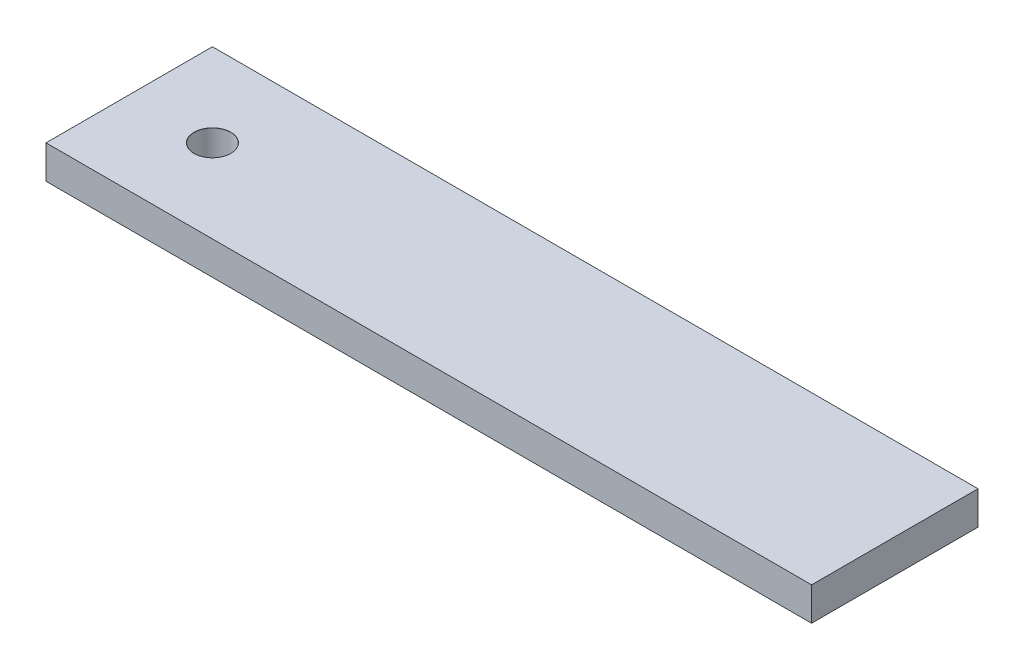
SolidWorks part; units mm, degrees
ref_plane "Front Plane" through (0, 0, 0) normal (0, 0, 1) x (1, 0, 0)
ref_plane "Top Plane" through (0, 0, 0) normal (0, 1, 0) x (1, 0, 0)
ref_plane "Right Plane" through (0, 0, 0) normal (1, 0, 0) x (0, 0, -1)
sketch "Sketch1" plane through (0, 0, 0) normal (0, 1, 0) x (1, 0, 0)
  line L1 (-115, 25) -> (115, 25)
  line L2 (-115, 25) -> (-115, -25)
  line L3 (-115, -25) -> (115, -25)
  line L4 (115, 25) -> (115, -25)
  line L5 (-115, 25) -> (115, -25) construction
  line L6 (-115, -25) -> (115, 25) construction
  point P0 (0, 0)
  dimension "D1" = 230
  dimension "D2" = 50
extrude "Boss-Extrude1" add sketch "Sketch1" along normal blind 10
sketch "Sketch7" plane through (0, 10, 0) normal (0, 1, 0) x (1, 0, 0)
  line L1 (-90, 0) -> (-90, 25) construction
  line L2 (115, 25) -> (-115, 25) construction
  line L4 (-90, 0) -> (-115, 0) construction
  line L5 (-115, 25) -> (-115, -25) construction
  point P0 (-90, 0)
hole_wizard "M10 Clearance Hole1" positions "Sketch7" profile "Sketch5" hole size "M10" standard "ANSI Metric" end condition through all
sketch "Sketch5" plane through (-90, 10, 0) normal (1, 0, 0) x (0, 0, 1)
  line L0 (0, 0) -> (0, 10)
  line L1 (0, 10) -> (5.5, 10)
  line L2 (5.5, 10) -> (5.5, 0.025)
  line L3 (5.5, 0.025) -> (5.525, 0)
  line L5 (5.525, 0) -> (0, 0)
  line L6 (-5.5, 0.025) -> (-5.525, 0) construction
  line L11 (0, -6.35) -> (0, 107.95) construction
  dimension "Thru Hole Dia." = 11
  dimension "Thru Hole Depth" = 10
  dimension "Near C'Sink Dia." = 11.05
  dimension "Near C'Sink Angle" = 90
